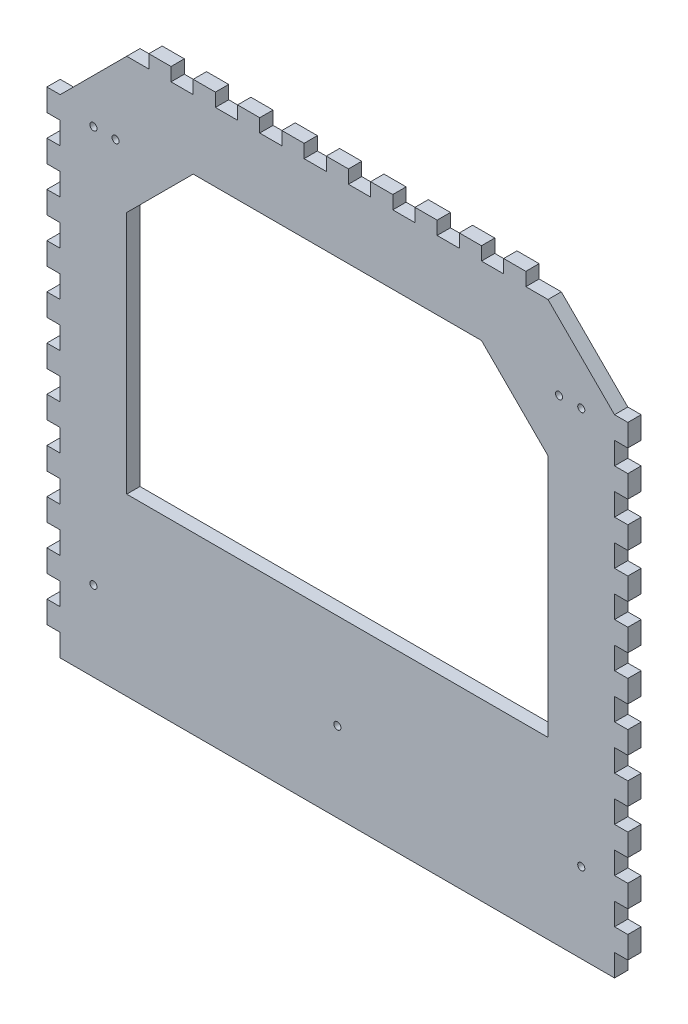
SolidWorks part; units mm, degrees
material "Buche"
ref_plane "Ebene vorne" through (0, 0, 0) normal (0, 0, 1) x (1, 0, 0)
ref_plane "Ebene oben" through (0, 0, 0) normal (0, 1, 0) x (1, 0, 0)
ref_plane "Ebene rechts" through (0, 0, 0) normal (1, 0, 0) x (0, 0, -1)
sketch "Skizze1" plane through (0, 0, 0) normal (0, 0, 1) x (1, 0, 0)
  line L0 (35, 250) -> (45, 250)
  line L1 (45, 250) -> (45, 256)
  line L2 (45, 256) -> (55, 256)
  line L3 (55, 256) -> (55, 250)
  line L4 (55, 250) -> (65, 250)
  line L5 (65, 250) -> (65, 256)
  line L6 (65, 256) -> (75, 256)
  line L7 (75, 256) -> (75, 250)
  line L8 (75, 250) -> (85, 250)
  line L9 (85, 250) -> (85, 256)
  line L10 (85, 256) -> (95, 256)
  line L11 (95, 256) -> (95, 250)
  line L12 (95, 250) -> (105, 250)
  line L13 (105, 250) -> (105, 256)
  line L14 (105, 256) -> (115, 256)
  line L15 (115, 256) -> (115, 250)
  line L16 (115, 250) -> (125, 250)
  line L17 (125, 250) -> (125, 256)
  line L18 (125, 256) -> (135, 256)
  line L19 (135, 256) -> (135, 250)
  line L20 (135, 250) -> (145, 250)
  line L21 (145, 250) -> (145, 256)
  line L22 (145, 256) -> (155, 256)
  line L23 (155, 256) -> (155, 250)
  line L24 (155, 250) -> (165, 250)
  line L25 (165, 250) -> (165, 256)
  line L26 (165, 256) -> (175, 256)
  line L27 (175, 256) -> (175, 250)
  line L28 (175, 250) -> (185, 250)
  line L29 (185, 250) -> (185, 256)
  line L30 (185, 256) -> (195, 256)
  line L31 (195, 256) -> (195, 250)
  line L32 (195, 250) -> (205, 250)
  line L33 (205, 250) -> (205, 256)
  line L34 (205, 256) -> (215, 256)
  line L35 (215, 256) -> (215, 250)
  line L36 (215, 250) -> (225, 250)
  line L37 (5, 30) -> (5, 20)
  line L38 (5, 40) -> (-1, 40)
  line L39 (-1, 30) -> (5, 30)
  line L40 (-1, 40) -> (-1, 30)
  line L41 (5, 50) -> (5, 40)
  line L42 (5, 60) -> (-1, 60)
  line L43 (-1, 50) -> (5, 50)
  line L44 (-1, 60) -> (-1, 50)
  line L45 (5, 70) -> (5, 60)
  line L46 (5, 80) -> (-1, 80)
  line L47 (-1, 70) -> (5, 70)
  line L48 (-1, 80) -> (-1, 70)
  line L49 (5, 90) -> (5, 80)
  line L50 (5, 100) -> (-1, 100)
  line L51 (-1, 90) -> (5, 90)
  line L52 (-1, 100) -> (-1, 90)
  line L53 (5, 110) -> (5, 100)
  line L54 (5, 120) -> (-1, 120)
  line L55 (-1, 110) -> (5, 110)
  line L56 (-1, 120) -> (-1, 110)
  line L57 (5, 130) -> (5, 120)
  line L58 (5, 140) -> (-1, 140)
  line L59 (-1, 130) -> (5, 130)
  line L60 (-1, 140) -> (-1, 130)
  line L61 (5, 150) -> (5, 140)
  line L62 (5, 160) -> (-1, 160)
  line L63 (-1, 150) -> (5, 150)
  line L64 (-1, 160) -> (-1, 150)
  line L65 (5, 170) -> (5, 160)
  line L66 (5, 180) -> (-1, 180)
  line L67 (-1, 170) -> (5, 170)
  line L68 (-1, 180) -> (-1, 170)
  line L69 (5, 190) -> (5, 180)
  line L70 (5, 200) -> (-1, 200)
  line L71 (-1, 190) -> (5, 190)
  line L72 (-1, 200) -> (-1, 190)
  line L73 (5, 210) -> (5, 200)
  line L74 (5, 220) -> (-1, 220)
  line L75 (-1, 210) -> (5, 210)
  line L76 (-1, 220) -> (-1, 210)
  line L77 (255, 40) -> (261, 40)
  line L78 (261, 40) -> (261, 30)
  line L79 (255, 30) -> (255, 20)
  line L80 (261, 30) -> (255, 30)
  line L81 (255, 60) -> (261, 60)
  line L82 (261, 60) -> (261, 50)
  line L83 (255, 50) -> (255, 40)
  line L84 (261, 50) -> (255, 50)
  line L85 (255, 80) -> (261, 80)
  line L86 (261, 80) -> (261, 70)
  line L87 (255, 70) -> (255, 60)
  line L88 (261, 70) -> (255, 70)
  line L89 (255, 100) -> (261, 100)
  line L90 (261, 100) -> (261, 90)
  line L91 (255, 90) -> (255, 80)
  line L92 (261, 90) -> (255, 90)
  line L93 (255, 120) -> (261, 120)
  line L94 (261, 120) -> (261, 110)
  line L95 (255, 110) -> (255, 100)
  line L96 (261, 110) -> (255, 110)
  line L97 (255, 140) -> (261, 140)
  line L98 (261, 140) -> (261, 130)
  line L99 (255, 130) -> (255, 120)
  line L100 (261, 130) -> (255, 130)
  line L101 (255, 160) -> (261, 160)
  line L102 (261, 160) -> (261, 150)
  line L103 (255, 150) -> (255, 140)
  line L104 (261, 150) -> (255, 150)
  line L105 (255, 180) -> (261, 180)
  line L106 (261, 180) -> (261, 170)
  line L107 (255, 170) -> (255, 160)
  line L108 (261, 170) -> (255, 170)
  line L109 (255, 200) -> (261, 200)
  line L110 (261, 200) -> (261, 190)
  line L111 (255, 190) -> (255, 180)
  line L112 (261, 190) -> (255, 190)
  line L113 (255, 220) -> (261, 220)
  line L114 (261, 220) -> (261, 210)
  line L115 (255, 210) -> (255, 200)
  line L116 (261, 210) -> (255, 210)
  line L200 (65, 218.9712) -> (195, 218.9712)
  line L207 (35, 78.9712) -> (35, 188.9712)
  line L214 (5, 220) -> (35, 250)
  line L224 (225, 188.9712) -> (195, 218.9712)
  line L241 (35, 78.9712) -> (225, 78.9712)
  line L252 (5, 0) -> (255, 0)
  line L253 (35, 188.9712) -> (65, 218.9712)
  line L263 (225, 78.9712) -> (225, 188.9712)
  line L274 (255, 220) -> (225, 250)
  line L284 (255, 20) -> (261, 20)
  line L285 (261, 20) -> (261, 10)
  line L287 (255, 10) -> (255, 0)
  line L288 (261, 10) -> (255, 10)
  line L290 (5, 10) -> (5, 0)
  line L291 (5, 20) -> (-1, 20)
  line L292 (-1, 10) -> (5, 10)
  line L293 (-1, 20) -> (-1, 10)
  circle A0 centre (20, 215) radius 1.6
  circle A1 centre (30, 215) radius 1.6
  circle A2 centre (240, 215) radius 1.6
  circle A3 centre (230, 215) radius 1.6
  circle A4 centre (20, 36) radius 1.6
  circle A5 centre (130, 36) radius 1.6
  circle A6 centre (240, 36) radius 1.6
  point P3 (-1, 0)
  dimension "D2" = 6
  dimension "D1" = 9
  dimension "D4" = 6
  dimension "D5" = 6
  dimension "D6" = 250
  dimension "D7" = 262
  dimension "D8" = 30
  dimension "D9" = 11
  dimension "D10" = 6
  dimension "D3" = 11
extrude "Aufsatz-Linear austragen1" add sketch "Skizze1" along normal blind 6
